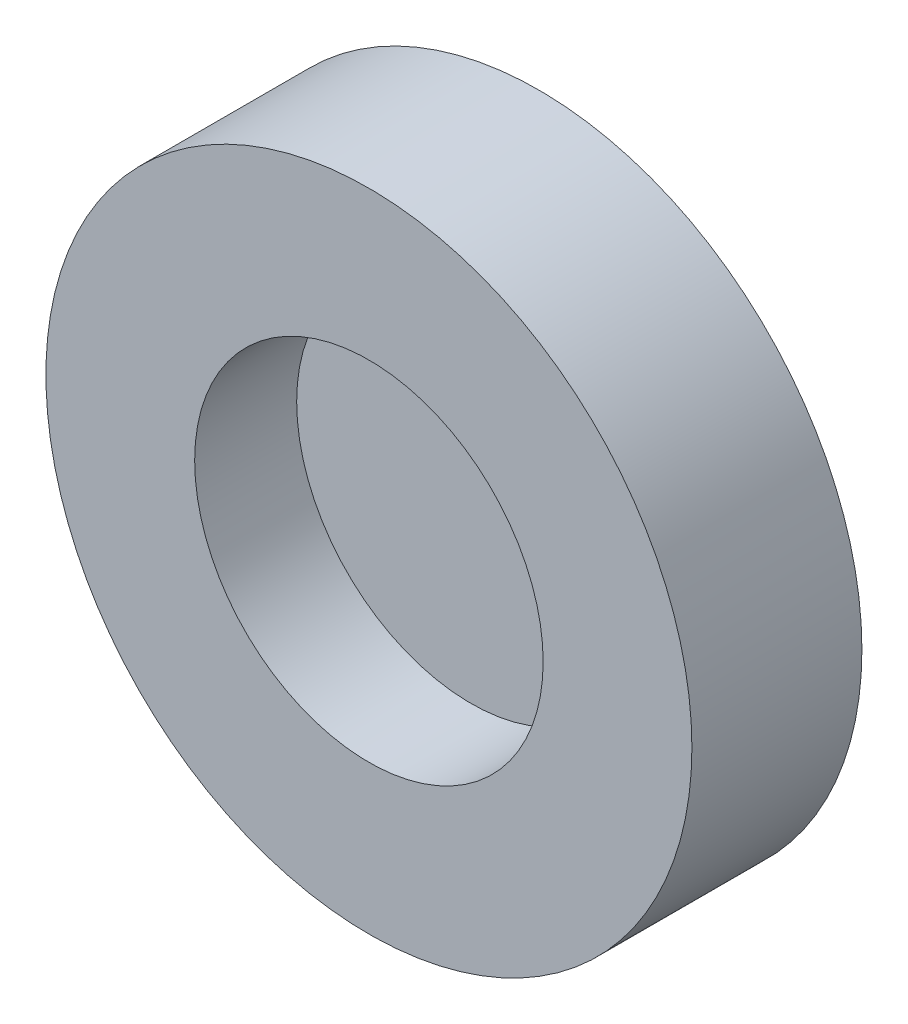
SolidWorks part; units mm, degrees
ref_plane "Plan de face" through (0, 0, 0) normal (0, 0, 1) x (1, 0, 0)
ref_plane "Plan de dessus" through (0, 0, 0) normal (0, 1, 0) x (1, 0, 0)
ref_plane "Plan de droite" through (0, 0, 0) normal (1, 0, 0) x (0, 0, -1)
sketch "Esquisse1" plane through (0, 0, 0) normal (0, 0, 1) x (1, 0, 0)
  circle A0 centre (0, 0) radius 19
  circle A1 centre (0, 0) radius 10.25
  dimension "D1" = 20.5
  dimension "D2" = 38
extrude "Boss.-Extru.1" add sketch "Esquisse1" along normal blind 10
sketch "Esquisse2" plane through (0, 0, 0) normal (0, 0, -1) x (-1, 0, 0)
  circle A0 centre (0, 0) radius 10.25
  circle A1 centre (0, 0) radius 10.25 construction
extrude "Boss.-Extru.2" add sketch "Esquisse2" against normal blind 4
